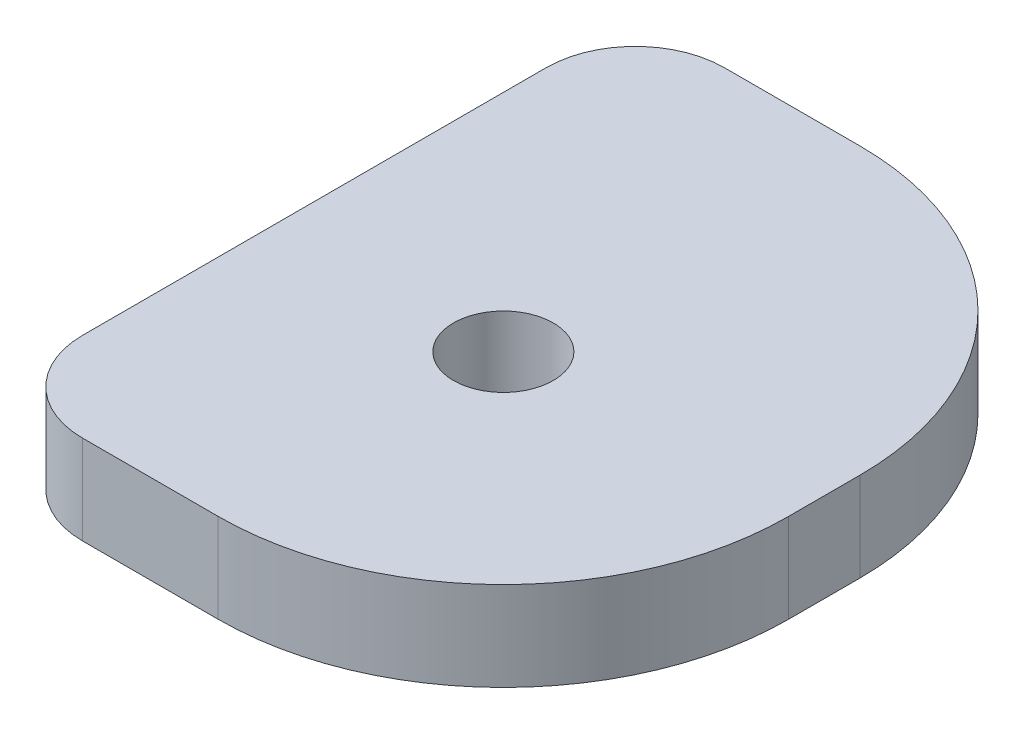
SolidWorks part; units mm, degrees
ref_plane "Front Plane" through (0, 0, 0) normal (0, 0, 1) x (1, 0, 0)
ref_plane "Top Plane" through (0, 0, 0) normal (0, 1, 0) x (1, 0, 0)
ref_plane "Right Plane" through (0, 0, 0) normal (1, 0, 0) x (0, 0, -1)
sketch "Sketch1" plane through (0, 0, 0) normal (0, 1, 0) x (1, 0, 0)
  line L1 (-25.4, 11.43) -> (25.4, 11.43)
  line L2 (-25.4, 11.43) -> (-25.4, -11.43)
  line L3 (-25.4, -11.43) -> (25.4, -11.43)
  line L4 (25.4, 11.43) -> (25.4, -11.43)
  dimension "D1" = 22.86
  dimension "D2" = 50.8
  dimension "D3" = 11.43
  dimension "D4" = 25.4
extrude "Boss-Extrude1" add sketch "Sketch1" along normal blind 3.175
fillet "Fillet1" radius 10.16 2 edges at (-25.4, 1.5875, 11.43) (25.4, 1.5875, 11.43)
sketch "Sketch3" plane through (0, 3.175, 0) normal (0, 1, 0) x (1, 0, 0)
  line L0 (-7.7526, -1.27) -> (18.5521, -1.27) construction
  circle A0 centre (15.24, -1.27) radius 1.778
  arc A2 (15.24, -11.43) -> (25.4, -1.27) centre (15.24, -1.27) ccw construction
  circle A3 centre (-3.81, -1.27) radius 1.778
  dimension "D1" = 3.556
  dimension "D6" = 3.556
  dimension "D5" = 19.05
extrude "Cut-Extrude1" cut sketch "Sketch3" against normal through all
fillet "Fillet3" radius 10.16 2 edges at (-25.4, 1.5875, -11.43) (25.4, 1.5875, -11.43)
sketch "Sketch4" plane through (0, 3.175, 0) normal (0, 1, 0) x (1, 0, 0)
  line L0 (7.239, 11.43) -> (7.239, -11.43)
  line L1 (-25.4, 1.27) -> (-25.4, -1.27) construction
  line L2 (7.239, 11.43) -> (-25.4, 11.43)
  line L5 (15.24, 11.43) -> (-15.24, 11.43) construction
  line L7 (-15.24, -11.43) -> (15.24, -11.43) construction
  line L9 (7.239, -11.43) -> (-25.4, -11.43)
  line L10 (-25.4, 11.43) -> (-25.4, -11.43)
  dimension "D1" = 18.161
extrude "Cut-Extrude2" cut sketch "Sketch4" against normal through all
fillet "Fillet9" radius 3.175 2 edges at (7.239, 1.5875, 11.43) (7.239, 1.5875, -11.43)
sketch "Sketch5" plane through (0, 3.175, 0) normal (0, 1, 0) x (1, 0, 0)
  line L0 (7.239, -8.255) -> (7.239, 8.255) construction
  line L1 (7.239, -0.4728) -> (14.0393, -0.4728)
  line L2 (7.239, -0.4728) -> (7.239, -1.6728)
  line L3 (7.239, -1.6728) -> (14.0393, -1.6728)
  line L4 (14.0393, -0.4728) -> (14.0393, -1.6728)
  line L5 (14.0393, -0.4728) -> (7.0393, -0.4728) construction
  line L6 (14.0393, -1.6728) -> (7.0393, -1.6728) construction
  line L10 (14.0393, -4.8228) -> (14.0393, 2.6772) construction
equation "\"D4@Sketch1\"=\"D2@Sketch1\"/2"
equation "\"D3@Sketch1\"=\"D1@Sketch1\"/2"
